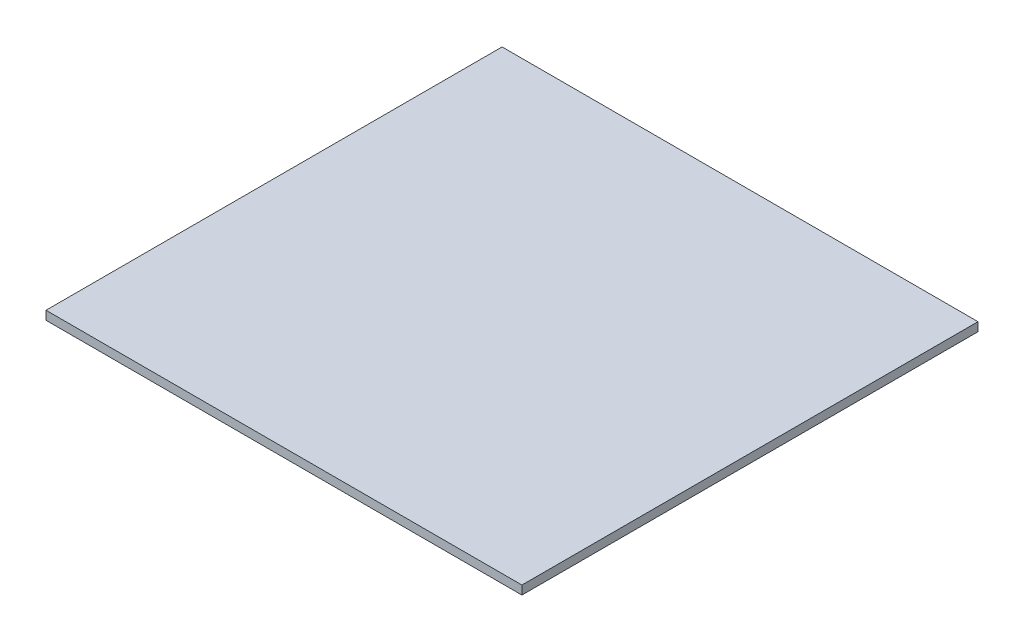
SolidWorks part; units mm, degrees
ref_plane "Front Plane" through (0, 0, 0) normal (0, 0, 1) x (1, 0, 0)
ref_plane "Top Plane" through (0, 0, 0) normal (0, 1, 0) x (1, 0, 0)
ref_plane "Right Plane" through (0, 0, 0) normal (1, 0, 0) x (0, 0, -1)
sketch "Sketch1" plane through (0, 0, 0) normal (0, 1, 0) x (1, 0, 0)
  line L1 (-152.4, -146.05) -> (152.4, -146.05)
  line L2 (-152.4, -146.05) -> (-152.4, 146.05)
  line L3 (-152.4, 146.05) -> (152.4, 146.05)
  line L4 (152.4, -146.05) -> (152.4, 146.05)
  line L5 (-152.4, -146.05) -> (152.4, 146.05) construction
  line L6 (-152.4, 146.05) -> (152.4, -146.05) construction
  point P0 (0, 0)
  dimension "D1" = 292.1
  dimension "D2" = 304.8
extrude "Boss-Extrude1" add sketch "Sketch1" along normal mid plane 5.588
